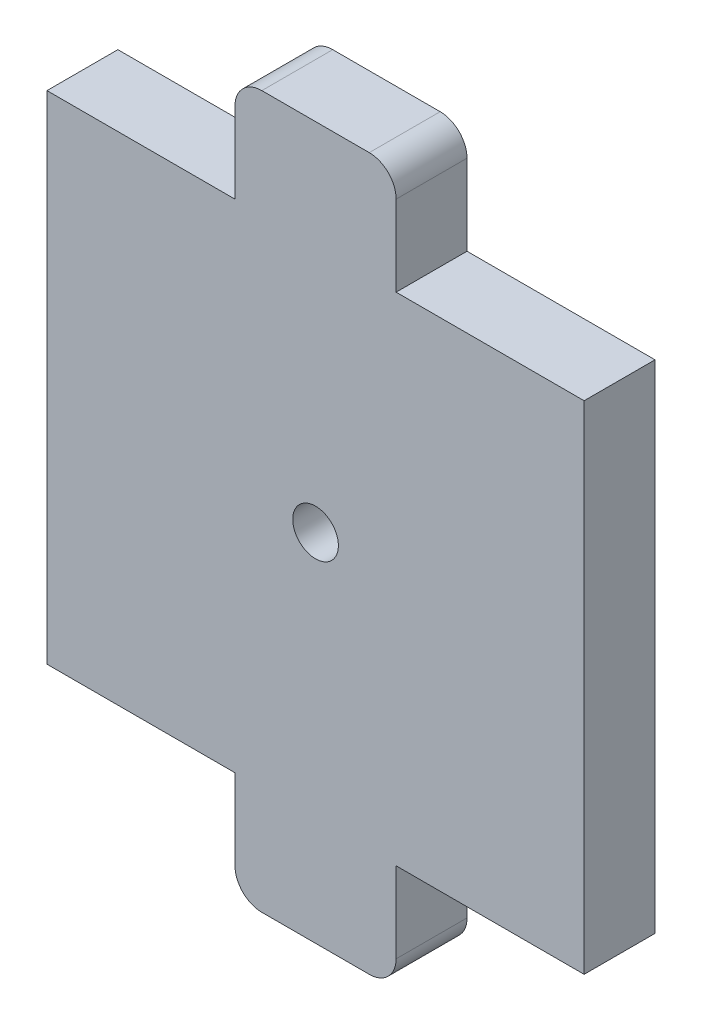
SolidWorks part; units mm, degrees
ref_plane "Front Plane" through (0, 0, 0) normal (0, 0, 1) x (1, 0, 0)
ref_plane "Top Plane" through (0, 0, 0) normal (0, 1, 0) x (1, 0, 0)
ref_plane "Right Plane" through (0, 0, 0) normal (1, 0, 0) x (0, 0, -1)
sketch "Model" plane through (0, 0, 0) normal (0, 0, 1) x (1, 0, 0)
  line L0 (-25, 23.12) -> (-25, -23.12)
  line L1 (-7.5, 23.12) -> (-25, 23.12)
  line L2 (-7.5, 30.62) -> (-7.5, 23.12)
  line L3 (5, 33.12) -> (-5, 33.12)
  line L4 (7.5, 23.12) -> (7.5, 30.62)
  line L5 (25, 23.12) -> (7.5, 23.12)
  line L6 (25, -23.12) -> (25, 23.12)
  line L7 (7.5, -23.12) -> (7.5, -30.62)
  line L8 (5, -33.12) -> (-5, -33.12)
  line L9 (-7.5, -30.62) -> (-7.5, -23.12)
  line L10 (7.5, -23.12) -> (25, -23.12)
  line L11 (-25, -23.12) -> (-7.5, -23.12)
  circle A0 centre (0, 0) radius 2.125
  arc A1 (-5, 33.12) -> (-7.5, 30.62) centre (-5, 30.62) ccw
  arc A2 (7.5, 30.62) -> (5, 33.12) centre (5, 30.62) ccw
  arc A3 (5, -33.12) -> (7.5, -30.62) centre (5, -30.62) ccw
  arc A4 (-7.5, -30.62) -> (-5, -33.12) centre (-5, -30.62) ccw
extrude "Boss-Extrude1" add sketch "Model" along normal blind 6.6
